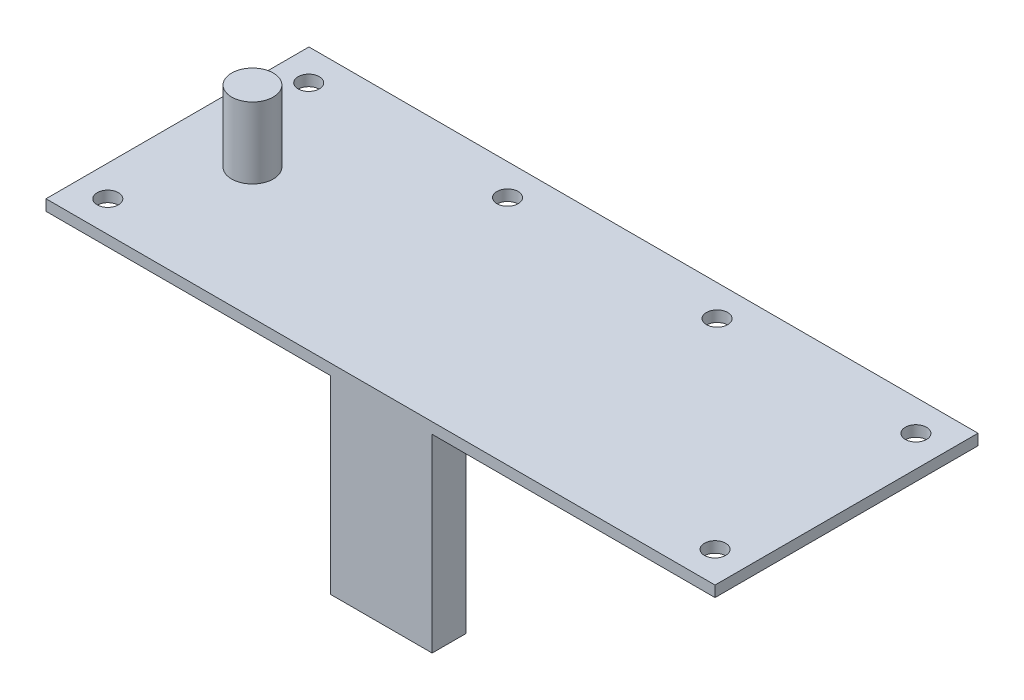
SolidWorks part; units mm, degrees
ref_plane "Front Plane" through (0, 0, 0) normal (0, 0, 1) x (1, 0, 0)
ref_plane "Top Plane" through (0, 0, 0) normal (0, 1, 0) x (1, 0, 0)
ref_plane "Right Plane" through (0, 0, 0) normal (1, 0, 0) x (0, 0, -1)
sketch "Sketch1" plane through (0, 0, 0) normal (0, 1, 0) x (1, 0, 0)
  line L1 (0, 0) -> (100.457, 0)
  line L2 (0, 0) -> (0, 39.4843)
  line L3 (0, 39.4843) -> (100.457, 39.4843)
  line L4 (100.457, 0) -> (100.457, 39.4843)
  circle A0 centre (4.6418, 34.8043) radius 1.5938
  circle A1 centre (34.4996, 34.8043) radius 1.5938
  circle A2 centre (4.6418, 4.6418) radius 1.5938
  circle A3 centre (65.9574, 34.8044) radius 1.5938
  circle A4 centre (95.8152, 34.8044) radius 1.5938
  circle A5 centre (95.8152, 4.6419) radius 1.5938
  dimension "D3" = 3.1877
  dimension "D4" = 3.0861
  dimension "D5" = 3.048
  dimension "D6" = 26.67
  dimension "D7" = 3.048
  dimension "D8" = 3.048
  dimension "D1" = 100.457
  dimension "D2" = 39.4843
ref_plane "Plane4" through (50.3618, 0, 0) normal (1, 0, 0) x (0, 0, -1)
extrude "Boss-Extrude1" add sketch "Sketch1" along normal blind 1.6383
sketch "Sketch3" plane through (0, 1.6383, 0) normal (0, 1, 0) x (1, 0, 0)
  line L2 (0, 39.4843) -> (0, 0) construction
  line L6 (0, 0) -> (100.457, 0) construction
  circle A0 centre (11.3792, 19.6215) radius 3.1242
  dimension "D1" = 14.5034
  dimension "D2" = 19.6215
  dimension "D3" = 6.2484
extrude "Boss-Extrude2" add sketch "Sketch3" along normal blind 10.668
sketch "Sketch4" plane through (0, 0, 0) normal (0, -1, 0) x (1, 0, 0)
  line L0 (0, 0) -> (100.457, 0) construction
  line L1 (57.9819, 0) -> (42.7418, 0)
  line L2 (57.9819, 0) -> (57.9818, -5.08)
  line L3 (57.9818, -5.08) -> (42.7418, -5.08)
  line L4 (42.7418, 0) -> (42.7418, -5.08)
  line L6 (50.3618, -6.7685) -> (50.3618, 6.7685) construction
  point P6 (50.3618, -5.08)
  dimension "D1" = 15.24
  dimension "D2" = 5.08
extrude "Boss-Extrude3" add sketch "Sketch4" along normal blind 28.448
